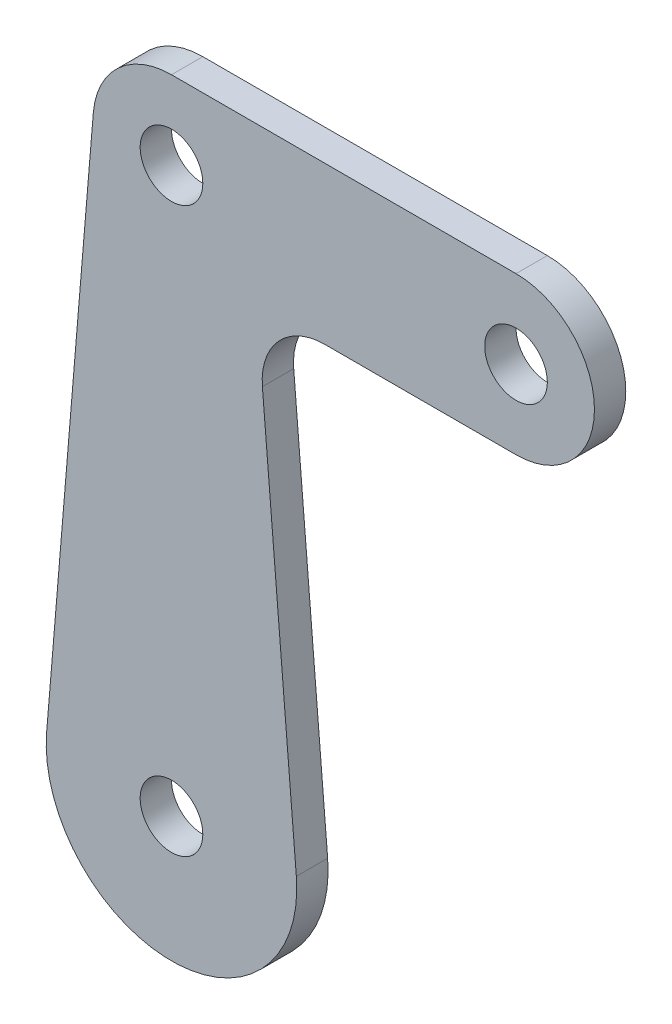
SolidWorks part; units mm, degrees
ref_plane "Front Plane" through (0, 0, 0) normal (0, 0, 1) x (1, 0, 0)
ref_plane "Top Plane" through (0, 0, 0) normal (0, 1, 0) x (1, 0, 0)
ref_plane "Right Plane" through (0, 0, 0) normal (1, 0, 0) x (0, 0, -1)
sketch "Sketch1" plane through (0, 0, 0) normal (0, 0, 1) x (1, 0, 0)
  line L0 (0, -57.15) -> (0, 0) construction
  line L1 (0, 0) -> (34.925, 0) construction
  line L2 (21.2239, -57.15) -> (-21.2239, -57.15) construction
  line L3 (-12.6561, -56.0945) -> (-7.9227, 0.6607)
  line L4 (0, 7.9502) -> (34.925, 7.9502)
  line L5 (34.925, -7.9502) -> (15.5425, -7.9502)
  line L6 (12.6561, -56.0945) -> (9.2144, -14.828)
  circle A0 centre (0, -57.15) radius 3.175
  arc A1 (-12.6561, -56.0945) -> (12.6561, -56.0945) centre (0, -57.15) ccw
  circle A2 centre (0, 0) radius 3.175
  circle A3 centre (34.925, 0) radius 3.175
  arc A4 (34.925, 7.9502) -> (34.925, -7.9502) centre (34.925, 0) cw
  arc A5 (-7.9227, 0.6607) -> (0, 7.9502) centre (0, 0) cw
  arc A6 (15.5425, -7.9502) -> (9.2144, -14.828) centre (15.5425, -14.3002) ccw
  point P9 (0, -57.15)
  point P19 (-8.2415, 2.1157)
  point P20 (0, 0)
  dimension "D1" = 25.4
  dimension "D3" = 6.35
  dimension "D5" = 7.9502
  dimension "D6" = 6.35
  dimension "D2" = 57.15
  dimension "D4" = 34.925
extrude "Boss-Extrude1" add sketch "Sketch1" along normal blind 3.175
